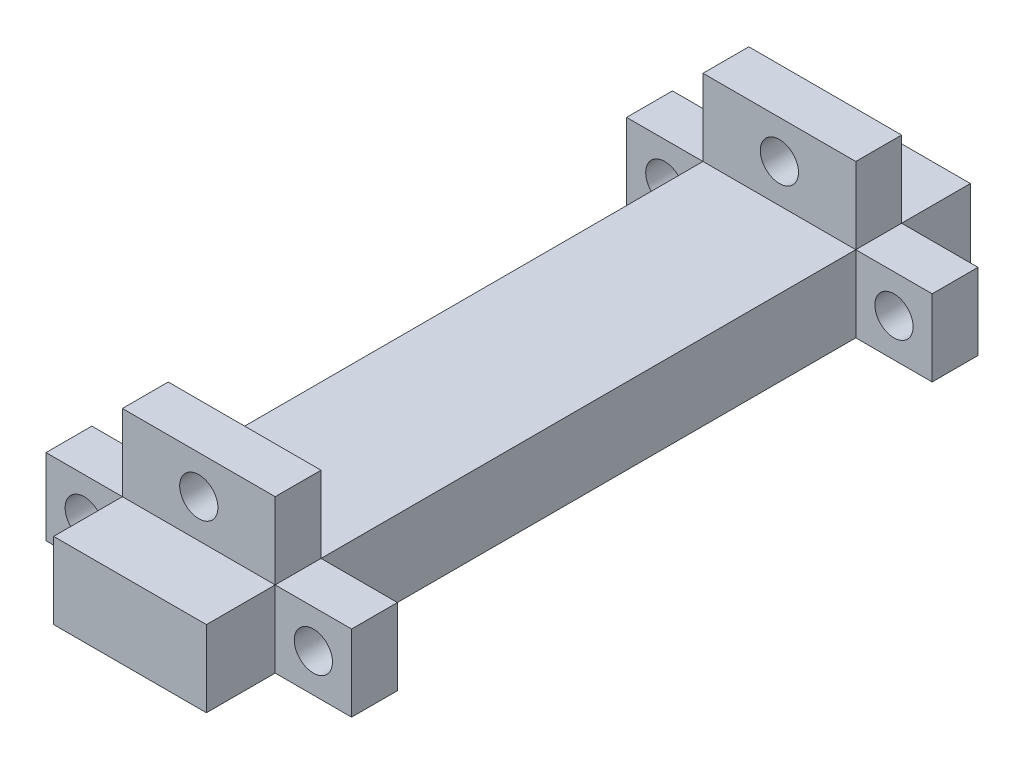
SolidWorks part; units mm, degrees
ref_plane "前视基准面" through (0, 0, 0) normal (0, 0, 1) x (1, 0, 0)
ref_plane "上视基准面" through (0, 0, 0) normal (0, 1, 0) x (1, 0, 0)
ref_plane "右视基准面" through (0, 0, 0) normal (1, 0, 0) x (0, 0, -1)
other "Configuration Table"
sketch "草图1" plane through (0, 0, 0) normal (0, 0, 1) x (1, 0, 0)
  line L1 (0, 0) -> (20, 0)
  line L2 (0, 0) -> (0, 10)
  line L3 (0, 10) -> (20, 10)
  line L4 (20, 0) -> (20, 10)
  dimension "D1" = 20
  dimension "D2" = 10
extrude "凸台-拉伸1" add sketch "草图1" along normal blind 100 contours L2 L3 L4 L1
sketch "草图2" plane through (0, 0, 0) normal (0, 0, -1) x (-1, 0, 0)
  line L1 (-20, 10) -> (0, 10)
  line L2 (-20, 10) -> (-20, 20)
  line L3 (-20, 20) -> (0, 20)
  line L4 (0, 10) -> (0, 20)
  line L5 (0, 0) -> (10, 0)
  line L6 (0, 0) -> (0, 10)
  line L7 (0, 10) -> (10, 10)
  line L8 (10, 0) -> (10, 10)
  line L9 (-20, 0) -> (-30, 0)
  line L10 (-20, 0) -> (-20, 10)
  line L11 (-20, 10) -> (-30, 10)
  line L12 (-30, 0) -> (-30, 10)
  line M12 (0, 10) -> (-20, 10)
  line M13 (-20, 10) -> (-20, 0)
  dimension "D1" = 10
  dimension "D2" = 10
ref_plane "基准面1" through (0, 0, 50) normal (0, 0, -1) x (-1, 0, 0)
extrude "凸台-拉伸2" add sketch "草图2" against normal blind 6 from offset 9 contours L12 L9 L11 M13 | L4 L3 L2 M12 | L6 L5 L8 L7 offset against normal yes
mirror "镜向1" about plane through (0, 0, 50) normal (0, 0, -1) of "凸台-拉伸2"
sketch "草图3" plane through (0, 0, 9) normal (0, 0, -1) x (-1, 0, 0)
  line L1 (-33.8025, 5) -> (20.2955, 5) construction
  line L2 (5, 14.7529) -> (5, -4.7529) construction
  line L3 (-25.6975, 15) -> (5.2513, 15) construction
  line L4 (-10, 22.4765) -> (-10, 13.0669) construction
  line L5 (0, 10) -> (0, 20) construction
  line L6 (-20, 10) -> (-20, 20) construction
  line L7 (-20, 20) -> (0, 20) construction
  line L8 (0, 10) -> (-20, 10) construction
  line L9 (0, 10) -> (10, 10) construction
  line L10 (0, 0) -> (10, 0) construction
  line L11 (10, 0) -> (10, 10) construction
  line L12 (0, 0) -> (0, 10) construction
  line L13 (-25, 12.0122) -> (-25, -3.7537) construction
  line L14 (-20, 0) -> (-20, 10) construction
  line L15 (-30, 0) -> (-30, 10) construction
  circle A0 centre (5, 5) radius 2.5
  circle A1 centre (-10, 15) radius 2.5
  circle A2 centre (-25, 5) radius 2.5
  point P36 (-26.6412, 5)
  dimension "D1" = 5
extrude "切除-拉伸1" cut sketch "草图3" against normal through all both and the other way through all
